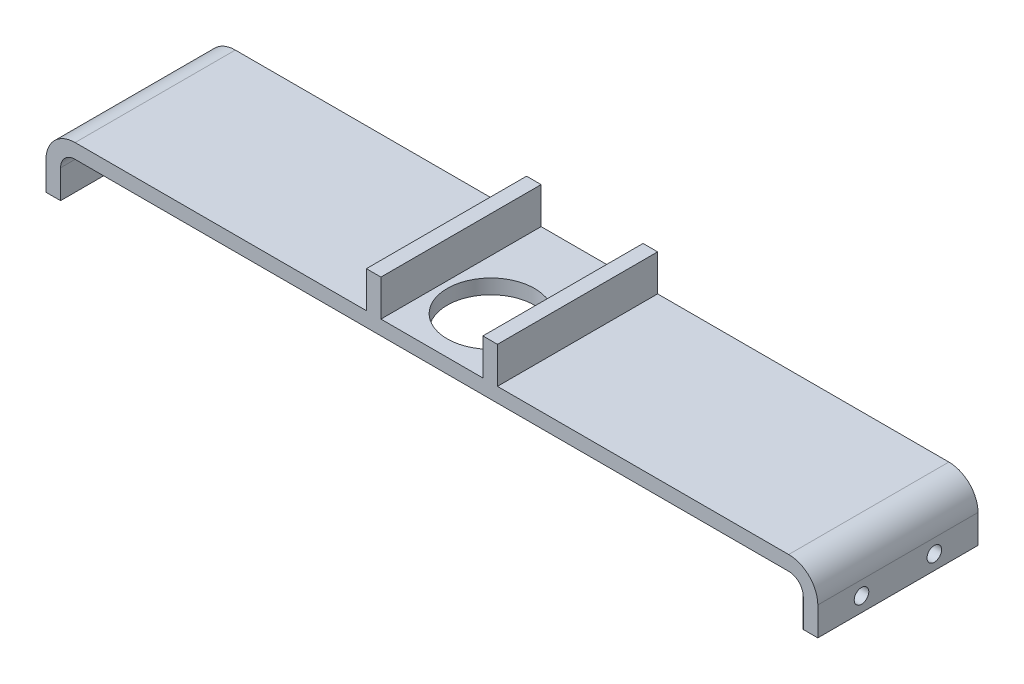
SolidWorks part; units mm, degrees
ref_plane "Front Plane" through (0, 0, 0) normal (0, 0, 1) x (1, 0, 0)
ref_plane "Top Plane" through (0, 0, 0) normal (0, 1, 0) x (1, 0, 0)
ref_plane "Right Plane" through (0, 0, 0) normal (1, 0, 0) x (0, 0, -1)
sketch "Sketch1" plane through (0, 0, 0) normal (0, 0, 1) x (1, 0, 0)
  line L0 (0, 0) -> (0, 19.6)
  line L3 (0, 19.6) -> (20, 19.6) construction
  line L4 (20, 19.6) -> (20, 39.6) construction
  line L5 (0, 0) -> (10, 0)
  line L6 (265, 0) -> (265, 41.1401) construction
  line L7 (20, 39.6) -> (510, 39.6)
  line L8 (530, 0) -> (530, 19.6)
  line L9 (0, 0) -> (10, 0)
  line L10 (20, 29.6) -> (510, 29.6)
  line L12 (10, 19.6) -> (10, 0)
  line L13 (520, 19.6) -> (520, 0)
  line L14 (520, 0) -> (530, 0)
  arc A2 (20, 39.6) -> (0, 19.6) centre (20, 19.6) ccw
  arc A3 (510, 39.6) -> (530, 19.6) centre (510, 19.6) cw
  arc A4 (20, 29.6) -> (10, 19.6) centre (20, 19.6) ccw
  arc A5 (510, 29.6) -> (520, 19.6) centre (510, 19.6) cw
  point P15 (265, 39.6)
  point P19 (265, 29.6)
  dimension "D1" = 19.6
  dimension "D2" = 20
  dimension "D4" = 530
extrude "Boss-Extrude2" add sketch "Sketch1" along normal blind 110 contours L10 A5 L13 L14 L8 A3 L7 A2 L0 L5 L12 A4
sketch "Sketch2" plane through (0, 0, 0) normal (-1, 0, 0) x (0, 0, 1)
  line L0 (110, 0) -> (0, 0) construction
  line L1 (0, 0) -> (0, 19.6) construction
  line L2 (55, 0) -> (55, 42.8019) construction
  circle A0 centre (30, 10) radius 5
  circle A1 centre (80, 10) radius 5
  dimension "D1" = 10
  dimension "D2" = 10
  dimension "D3" = 30
extrude "Cut-Extrude1" cut sketch "Sketch2" against normal through all
sketch "Sketch3" plane through (0, 39.6, 0) normal (0, 1, 0) x (1, 0, 0)
  line L0 (265, -110) -> (265, -104.5686)
  line L1 (20, -110) -> (510, -110) construction
  line L2 (265, -110) -> (230, -110)
  line L3 (265, -110) -> (300, -110)
  line L4 (230, -110) -> (230, 0)
  line L5 (300, -110) -> (300, 0)
  line L6 (230, 0) -> (220, 0)
  line L7 (220, 0) -> (220, -110)
  line L8 (300, 0) -> (310, 0)
  line L9 (310, 0) -> (310, -110)
  line L10 (220, -110) -> (230, -110)
  line L11 (300, -110) -> (310, -110)
  line M9 (20, -110) -> (510, -110)
  dimension "D1" = 45
  dimension "D2" = 45
  dimension "D3" = 10
  dimension "D4" = 110
  dimension "D5" = 10
  dimension "D6" = 110
extrude "Boss-Extrude3" add sketch "Sketch3" along normal blind 25 contours L6 L7 L4 M9 | L5 L8 L9 L11
sketch "Sketch4" plane through (0, 64.6, 0) normal (0, 1, 0) x (1, 0, 0)
  line L0 (220, 0) -> (230, 0)
  line L1 (230, -110) -> (230, 0) construction
  line L2 (230, 0) -> (300, 0) construction
  line L3 (230, 0) -> (230, -8.4974)
  line L4 (230, -8.4974) -> (220, -8.4974)
  line L5 (220, 0) -> (220, -110) construction
  line L6 (220, -8.4974) -> (220, 0)
sketch "Sketch5" plane through (0, 39.6, 0) normal (0, 1, 0) x (1, 0, 0)
  line L0 (264.5009, -39) -> (246.105, -39)
  line L1 (230, -110) -> (300, -110) construction
  circle A0 centre (264.5009, -69) radius 30
  dimension "D1" = 71
  dimension "D2" = 60
extrude "Cut-Extrude2" cut sketch "Sketch5" against normal through all contours A0
sketch "Sketch6" plane through (0, 0, 0) normal (0, 0, -1) x (-1, 0, 0)
  line L0 (-300, 64.6) -> (-300, 69.6)
  line L1 (-310, 64.6) -> (-310, 72.6)
  line L2 (-230, 64.6) -> (-230, 69.6)
  line L3 (-220, 64.6) -> (-220, 72.6)
  line L4 (-305, 77.6) -> (-225, 77.6)
  line L5 (-295, 74.6) -> (-235, 74.6)
  line L6 (-310, 64.6) -> (-300, 64.6)
  line L7 (-230, 64.6) -> (-220, 64.6)
  arc A0 (-220, 72.6) -> (-225, 77.6) centre (-225, 72.6) ccw
  arc A1 (-305, 77.6) -> (-310, 72.6) centre (-305, 72.6) ccw
  arc A2 (-230, 69.6) -> (-235, 74.6) centre (-235, 69.6) ccw
  arc A3 (-295, 74.6) -> (-300, 69.6) centre (-295, 69.6) ccw
  point P15 (-220, 77.6)
  point P18 (-310, 77.6)
  point P23 (-300, 74.6)
  dimension "D4" = 5
  dimension "D5" = 5
  dimension "D1" = 10
  dimension "D2" = 13
  dimension "D3" = 13
